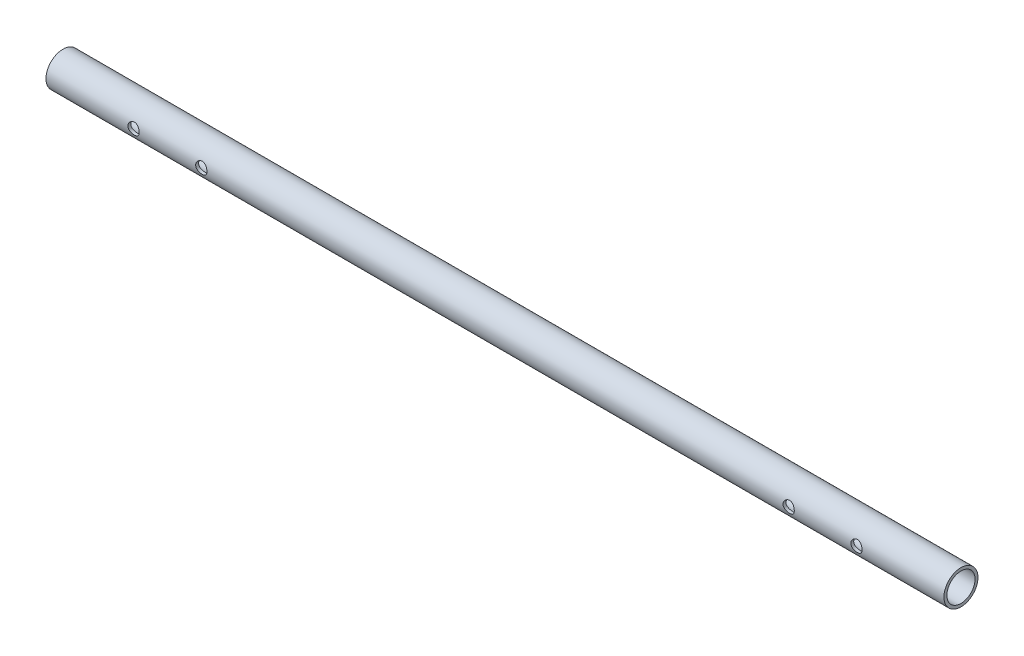
SolidWorks part; units mm, degrees
material "AISI 304"
ref_plane "Front Plane" through (0, 0, 0) normal (0, 0, 1) x (1, 0, 0)
ref_plane "Top Plane" through (0, 0, 0) normal (0, 1, 0) x (1, 0, 0)
ref_plane "Right Plane" through (0, 0, 0) normal (1, 0, 0) x (0, 0, -1)
sketch "Sketch1" plane through (0, 0, 0) normal (1, 0, 0) x (0, 0, -1)
  circle A0 centre (0, 0) radius 30.15
  circle A1 centre (0, 0) radius 24.9
  dimension "D1" = 60.3
  dimension "D2" = 49.8
extrude "Boss-Extrude1" add sketch "Sketch1" along normal mid plane 1590
sketch "Sketch5" plane through (0, 0, 0) normal (0, 0, 1) x (1, 0, 0)
  line L0 (-795, 30.15) -> (-795, -30.15) construction
  circle A0 centre (-520, 0) radius 10
  circle A1 centre (-640, 0) radius 10
  dimension "D2" = 155
  dimension "D3" = 20
  dimension "D1" = 120
extrude "Cut-Extrude2" cut sketch "Sketch5" against normal through all both and the other way through all
mirror "Mirror1" about plane through (0, 0, 0) normal (1, 0, 0) of "Cut-Extrude2"
